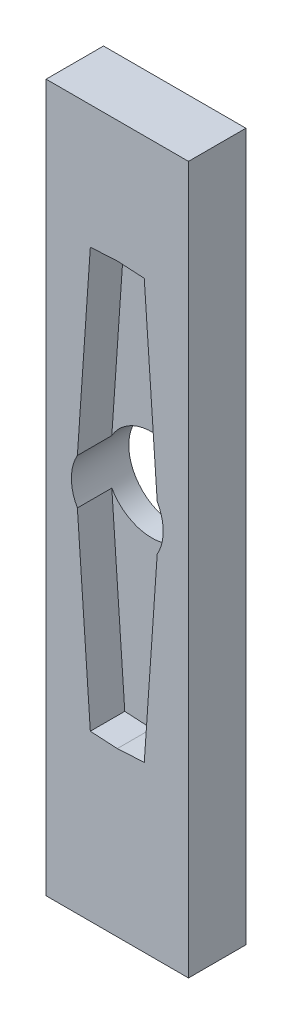
SolidWorks part; units mm, degrees
ref_plane "Front Plane" through (0, 0, 0) normal (0, 0, 1) x (1, 0, 0)
ref_plane "Top Plane" through (0, 0, 0) normal (0, 1, 0) x (1, 0, 0)
ref_plane "Right Plane" through (0, 0, 0) normal (1, 0, 0) x (0, 0, -1)
sketch "Sketch1" plane through (0, 0, 0) normal (0, 0, 1) x (1, 0, 0)
  line L0 (6.2, -29) -> (6.2, -32.59)
  line L2 (6.2, -29) -> (6.2, 29)
  line L3 (6.2, 29) -> (-6.2, 29)
  line L4 (-6.2, -29) -> (-6.2, 29)
  line L5 (6.2, -29) -> (-6.2, 29) construction
  line L6 (6.2, 29) -> (-6.2, -29) construction
  line L7 (6.2, -32.59) -> (-6.2, -32.59)
  line L8 (-6.2, -32.59) -> (-6.2, -29)
  point P0 (0, 0)
  dimension "D1" = 58
  dimension "D2" = 12.4
  dimension "D3" = 3.59
extrude "Boss-Extrude1" add sketch "Sketch1" against normal blind 5
sketch "Sketch2" plane through (0, 0, 0) normal (0, 0, 1) x (1, 0, 0)
  line L2 (0, 0) -> (9.4422, 0) construction
  line L7 (-3.6138, 0) -> (-2.3482, 18.2538)
  line L8 (0, 18.3878) -> (-2.3482, 18.2538)
  line L9 (0, 0) -> (0, 19.7752) construction
  line L10 (3.6138, 0) -> (2.3482, 18.2538)
  line L11 (0, 18.3878) -> (2.3482, 18.2538)
  line L12 (0, -18.3878) -> (2.3482, -18.2538)
  line L13 (3.6138, 0) -> (2.3482, -18.2538)
  line L14 (0, -18.3878) -> (-2.3482, -18.2538)
  line L15 (-3.6138, 0) -> (-2.3482, -18.2538)
extrude "Cut-Extrude1" cut sketch "Sketch2" against normal blind 3
sketch "Sketch4" plane through (0, 0, 0) normal (0, 0, 1) x (1, 0, 0)
  circle A0 centre (0, 0) radius 4
  dimension "D1" = 8
extrude "Cut-Extrude2" cut sketch "Sketch4" against normal blind 5
